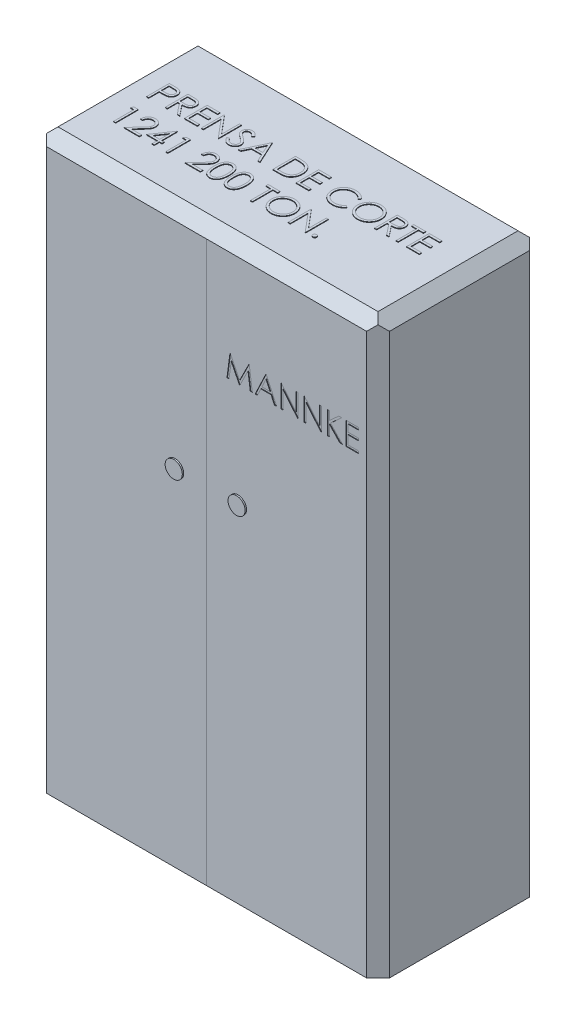
SolidWorks part; units mm, degrees
ref_plane "Alzado" through (0, 0, 0) normal (0, 0, 1) x (1, 0, 0)
ref_plane "Planta" through (0, 0, 0) normal (0, 1, 0) x (1, 0, 0)
ref_plane "Vista lateral" through (0, 0, 0) normal (1, 0, 0) x (0, 0, -1)
sketch "Croquis1" plane through (0, 0, 0) normal (0, 1, 0) x (1, 0, 0)
  line L1 (-600, 285) -> (600, 285)
  line L2 (-600, 285) -> (-600, -285)
  line L3 (-600, -285) -> (600, -285)
  line L4 (600, 285) -> (600, -285)
  line L5 (-600, 285) -> (600, -285) construction
  line L6 (-600, -285) -> (600, 285) construction
  point P0 (0, 0)
  dimension "D1" = 1200
  dimension "D2" = 570
extrude "Saliente-Extruir1" add sketch "Croquis1" along normal blind 2000
sketch "Croquis2" plane through (0, 0, 285) normal (0, 0, 1) x (1, 0, 0)
  line L0 (0, 2000) -> (0, 0)
  line L1 (-600, 2000) -> (600, 2000) construction
extrude "Cortar-Extruir1" cut sketch "Croquis2" against normal blind 0.1 and the other way through all
sketch "Croquis3" plane through (0, 0, 285) normal (0, 0, 1) x (1, 0, 0)
  line L0 (-600, 1000) -> (600, 1000) construction
  line L1 (-600, 2000) -> (-600, 0) construction
  line L2 (600, 2000) -> (600, 0) construction
  line L3 (0, 0) -> (0, 2000) construction
  line L4 (0, 0) -> (0, 2000) construction
  circle A0 centre (-110, 1209.492) radius 30
  circle A1 centre (110, 1209.492) radius 30
  dimension "D3" = 60
  dimension "D4" = 60
  dimension "D1" = 110
  dimension "D2" = 110
extrude "Saliente-Extruir2" add sketch "Croquis3" along normal blind 5
chamfer "Chaflán1" distance 40 angle 45 1 edges at (-600, 1000, 285)
chamfer "Chaflán2" distance 40 angle 45 1 edges at (-280, 2000, 285)
chamfer "Chaflán3" distance 40 angle 45 1 edges at (600, 980.05, 284.9)
chamfer "Chaflán4" distance 40 angle 45 1 edges at (600, 2000, -20.05)
chamfer "Chaflán5" distance 40 angle 45 1 edges at (600, 980, -285)
chamfer "Chaflán6" distance 40 angle 45 1 edges at (-20, 2000, -285)
chamfer "Chaflán7" distance 40 angle 45 1 edges at (-600, 980, -285)
chamfer "Chaflán8" distance 40 angle 45 1 edges at (-600, 2000, 0)
sketch "Croquis4" plane through (0, 0, 284.9) normal (0, 0, 1) x (1, 0, 0)
  line L0 (65.1996, 1575.2008) -> (528.8464, 1575.2008) construction
  text T0 "MANNKE" font "Century Gothic" height in points 300
extrude "Cortar-Extruir2" cut sketch "Croquis4" against normal blind 2
sketch "Croquis5" plane through (0, 2000, 0) normal (0, 1, 0) x (1, 0, 0)
  line L0 (-504.9124, 0) -> (517.2273, 0) construction
  text T0 "PRENSA DE CORTE \r\n1241 200 TON." font "Century Gothic" height in points 300
extrude "Saliente-Extruir3" add sketch "Croquis5" along normal blind 2
